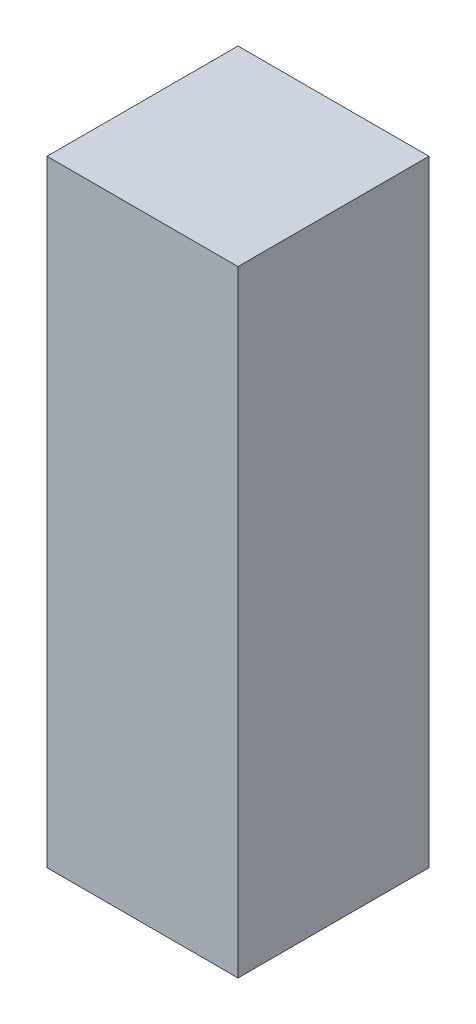
SolidWorks part; units mm, degrees
ref_plane "Front Plane" through (0, 0, 0) normal (0, 0, 1) x (1, 0, 0)
ref_plane "Top Plane" through (0, 0, 0) normal (0, 1, 0) x (1, 0, 0)
ref_plane "Right Plane" through (0, 0, 0) normal (1, 0, 0) x (0, 0, -1)
sketch "Sketch2" plane through (0, 0, 0) normal (0, 1, 0) x (1, 0, 0)
  line L1 (-31, 31) -> (31, 31)
  line L2 (-31, 31) -> (-31, -31)
  line L3 (-31, -31) -> (31, -31)
  line L4 (31, 31) -> (31, -31)
  line L5 (-31, 31) -> (31, -31) construction
  line L6 (-31, -31) -> (31, 31) construction
  point P0 (0, 0)
  dimension "D1" = 62
  dimension "D2" = 62
extrude "Boss-Extrude1" add sketch "Sketch2" along normal blind 200
